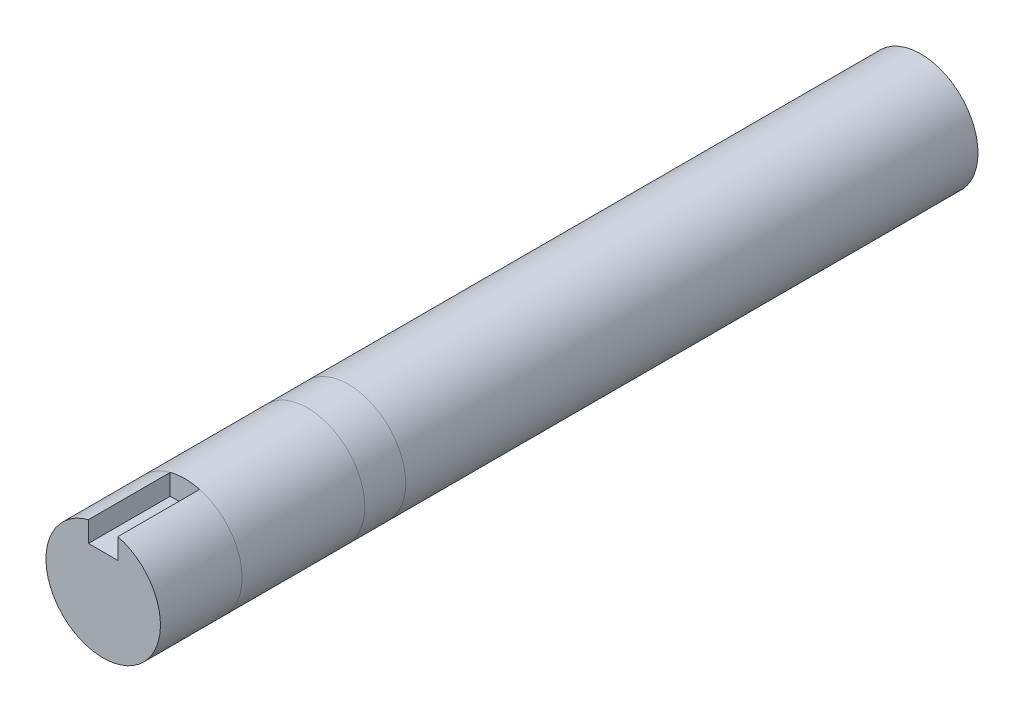
SolidWorks part; units mm, degrees
material "1023 Carbon Steel Sheet (SS)"
ref_plane "Front Plane" through (0, 0, 0) normal (0, 0, 1) x (1, 0, 0)
ref_plane "Top Plane" through (0, 0, 0) normal (0, 1, 0) x (1, 0, 0)
ref_plane "Right Plane" through (0, 0, 0) normal (1, 0, 0) x (0, 0, -1)
sketch "Sketch1" plane through (0, 0, 0) normal (0, 0, 1) x (1, 0, 0)
  circle A0 centre (0, 0) radius 70
  dimension "D1" = 140
extrude "Boss-Extrude1" add sketch "Sketch1" against normal blind 1000
sketch "Sketch3" plane through (0, 0, 0) normal (0, 0, 1) x (1, 0, 0)
  line L1 (-18, 42.4) -> (18, 42.4)
  line L2 (-18, 42.4) -> (-18, 78.4)
  line L3 (-18, 78.4) -> (18, 78.4)
  line L4 (18, 42.4) -> (18, 78.4)
  line L5 (-18, 42.4) -> (18, 78.4) construction
  line L6 (-18, 78.4) -> (18, 42.4) construction
  point P0 (0, 60.4)
  dimension "D1" = 36
  dimension "D2" = 78.4
extrude "Cut-Extrude1" cut sketch "Sketch3" against normal blind 100
ref_plane "Plane1" through (0, 0, -300) normal (0, 0, 1) x (1, 0, 0)
sketch "Sketch5" plane through (0, 0, -300) normal (0, 0, 1) x (1, 0, 0)
  circle A0 centre (0, 0) radius 70
  dimension "D1" = 140
extrude "Extrude-Thin1" add sketch "Sketch5" along normal blind 50 thin thin type one direction wall 0.0001
sketch "Sketch6" plane through (0, 0, 0) normal (0, 1, 0) x (1, 0, 0)
  line L0 (78.8086, 99.8797) -> (-76.2919, 99.8797)
split line "Split Line1"
